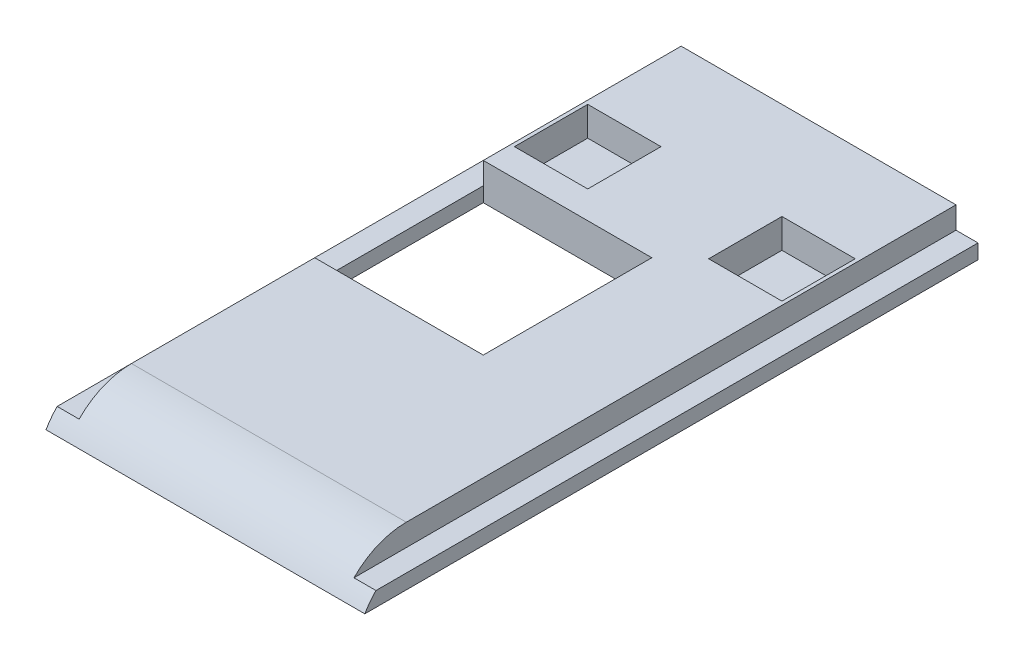
SolidWorks part; units mm, degrees
ref_plane "Přední rovina" through (0, 0, 0) normal (0, 0, 1) x (1, 0, 0)
ref_plane "Horní rovina" through (0, 0, 0) normal (0, 1, 0) x (1, 0, 0)
ref_plane "Pravá rovina" through (0, 0, 0) normal (1, 0, 0) x (0, 0, -1)
sketch "Skica1" plane through (0, 0, 0) normal (0, 1, 0) x (1, 0, 0)
  line L5 (0, 0) -> (17.4, 0)
  line L6 (0, 0) -> (0, 27)
  line L7 (0, 27) -> (17.4, 27)
  line L8 (17.4, 0) -> (17.4, 27)
  dimension "D1" = 27
  dimension "D2" = 17.4
extrude "Přidat vysunutím1" add sketch "Skica1" along normal blind 2
sketch "Skica2" plane through (0, 0, 0) normal (0, -1, 0) x (1, 0, 0)
  line L1 (0, 0) -> (17.4, 0)
  line L2 (0, 0) -> (0, -27)
  line L3 (0, -27) -> (17.4, -27)
  line L4 (17.4, 0) -> (17.4, -27)
extrude "Přidat vysunutím2" add sketch "Skica2" along normal blind 6
fillet "Zaoblit1" radius 4 1 edges at (8.7, 2, 0)
sketch "Skica3" plane through (0, -6, 0) normal (0, -1, 0) x (1, 0, 0)
  line L1 (0, 0) -> (17.4, 0)
  line L2 (0, 0) -> (0, -27)
  line L3 (0, -27) -> (17.4, -27)
  line L4 (17.4, 0) -> (17.4, -27)
extrude "Odebrat vysunutím1" cut sketch "Skica3" against normal blind 6
sketch "Skica4" plane through (0, 2, 0) normal (0, 1, 0) x (1, 0, 0)
  line L0 (0, 0.5359) -> (17.4, 0.5359) construction
  line L1 (0, 27) -> (1.2, 27)
  line L2 (0, 27) -> (0, 0.5359)
  line L3 (0, 0.5359) -> (1.2, 0.5359)
  line L4 (1.2, 27) -> (1.2, 0.5359)
  line L6 (17.4, 27) -> (16.2, 27)
  line L7 (17.4, 27) -> (17.4, 0.5359)
  line L8 (17.4, 0.5359) -> (16.2, 0.5359)
  line L9 (16.2, 27) -> (16.2, 0.5359)
  dimension "D1" = 1.2
  dimension "D2" = 1.2
extrude "Odebrat vysunutím2" cut sketch "Skica4" against normal blind 1.2
sketch "Skica7" plane through (0, 0, -27) normal (0, 0, -1) x (-1, 0, 0)
  line L1 (-16.2, 2) -> (-1.2, 2)
  line L2 (-16.2, 2) -> (-16.2, 0.8)
  line L3 (-16.2, 0.8) -> (-1.2, 0.8)
  line L4 (-1.2, 2) -> (-1.2, 0.8)
  line L5 (-17.4, 0.8) -> (0, 0.8)
  line L6 (-17.4, 0.8) -> (-17.4, 0)
  line L7 (-17.4, 0) -> (0, 0)
  line L8 (0, 0.8) -> (0, 0)
extrude "Přidat vysunutím3" add sketch "Skica7" along normal blind 7 contours L3 L4 L1 L2 | L7 L8 L5 L6
sketch "Skica8" plane through (0, 2, 0) normal (0, 1, 0) x (1, 0, 0)
  line L0 (1.2, 34) -> (1.2, 4) construction
  line L1 (1.2, 23.2) -> (10.4, 23.2)
  line L2 (1.2, 23.2) -> (1.2, 14)
  line L3 (1.2, 14) -> (10.4, 14)
  line L4 (10.4, 23.2) -> (10.4, 14)
  line L5 (16.2, 34) -> (1.2, 34) construction
  dimension "D1" = 9.2
  dimension "D2" = 20
extrude "Odebrat vysunutím5" cut sketch "Skica8" against normal blind 7
sketch "Skica10" plane through (0, 2, 0) normal (0, 1, 0) x (1, 0, 0)
  line L0 (1.2, 23.2) -> (1.2, 34) construction
  line L1 (1.4, 28.7) -> (5.4, 28.7)
  line L2 (1.4, 28.7) -> (1.4, 24.7)
  line L3 (1.4, 24.7) -> (5.4, 24.7)
  line L4 (5.4, 28.7) -> (5.4, 24.7)
  line L5 (12, 28.7) -> (16, 28.7)
  line L6 (12, 28.7) -> (12, 24.7)
  line L7 (12, 24.7) -> (16, 24.7)
  line L8 (16, 28.7) -> (16, 24.7)
  line L9 (16.2, 34) -> (16.2, 4) construction
  line L10 (10.4, 23.2) -> (1.2, 23.2) construction
  dimension "D1" = 4
  dimension "D2" = 4
  dimension "D3" = 0.2
  dimension "D4" = 0.2
  dimension "D5" = 1.5
  dimension "D6" = 1.5
extrude "Odebrat vysunutím6" cut sketch "Skica10" against normal blind 1.6
